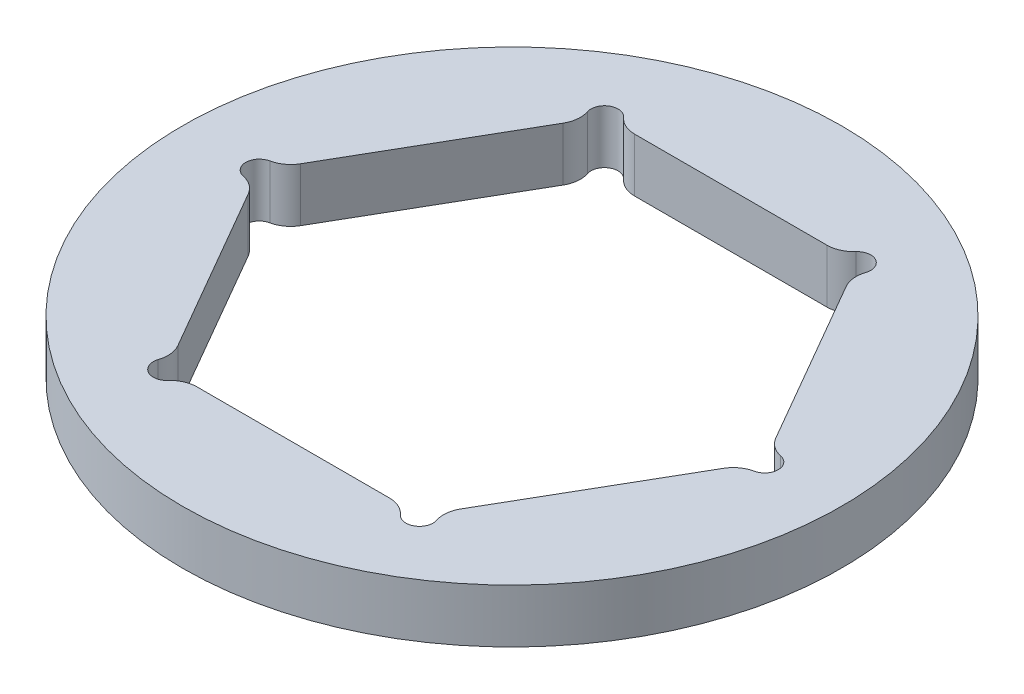
SolidWorks part; units mm, degrees
material "ABS"
ref_plane "Alzado" through (0, 0, 0) normal (0, 0, 1) x (1, 0, 0)
ref_plane "Planta" through (0, 0, 0) normal (0, 1, 0) x (1, 0, 0)
ref_plane "Vista lateral" through (0, 0, 0) normal (1, 0, 0) x (0, 0, -1)
sketch "Croquis1" plane through (0, 0, 0) normal (0, 1, 0) x (1, 0, 0)
  line L1 (4.1867, -5.7024) -> (7.0318, -0.7746)
  line L2 (7.0318, 0.7746) -> (4.1867, 5.7024)
  line L3 (2.8451, 6.477) -> (-2.8451, 6.477)
  line L4 (-4.1867, 5.7024) -> (-7.0318, 0.7746)
  line L5 (-7.0318, -0.7746) -> (-4.1867, -5.7024)
  line L6 (-2.8451, -6.477) -> (2.8451, -6.477)
  circle A0 centre (0, 0) radius 9.7536
  circle A1 centre (0, 0) radius 6.477 construction
  arc A2 (-3.4414, 6.7437) -> (-4.1195, 6.3521) centre (-3.7395, 6.477) ccw
  arc A3 (-3.4414, 6.7437) -> (-2.8451, 6.477) centre (-2.8451, 7.277) ccw
  arc A4 (-4.1867, 5.7024) -> (-4.1195, 6.3521) centre (-4.8795, 6.1024) ccw
  arc A5 (4.1195, 6.3521) -> (3.4414, 6.7437) centre (3.7395, 6.477) ccw
  arc A6 (4.1195, 6.3521) -> (4.1867, 5.7024) centre (4.8795, 6.1024) ccw
  arc A7 (2.8451, 6.477) -> (3.4414, 6.7437) centre (2.8451, 7.277) ccw
  arc A8 (7.5609, -0.3915) -> (7.5609, 0.3915) centre (7.479, 0) ccw
  arc A9 (7.5609, -0.3915) -> (7.0318, -0.7746) centre (7.7246, -1.1746) ccw
  arc A10 (7.0318, 0.7746) -> (7.5609, 0.3915) centre (7.7246, 1.1746) ccw
  arc A11 (3.4414, -6.7437) -> (4.1195, -6.3521) centre (3.7395, -6.477) ccw
  arc A12 (3.4414, -6.7437) -> (2.8451, -6.477) centre (2.8451, -7.277) ccw
  arc A13 (4.1867, -5.7024) -> (4.1195, -6.3521) centre (4.8795, -6.1024) ccw
  arc A14 (-4.1195, -6.3521) -> (-3.4414, -6.7437) centre (-3.7395, -6.477) ccw
  arc A15 (-4.1195, -6.3521) -> (-4.1867, -5.7024) centre (-4.8795, -6.1024) ccw
  arc A16 (-2.8451, -6.477) -> (-3.4414, -6.7437) centre (-2.8451, -7.277) ccw
  arc A17 (-7.5609, 0.3915) -> (-7.5609, -0.3915) centre (-7.479, 0) ccw
  arc A18 (-7.5609, 0.3915) -> (-7.0318, 0.7746) centre (-7.7246, 1.1746) ccw
  arc A19 (-7.0318, -0.7746) -> (-7.5609, -0.3915) centre (-7.7246, -1.1746) ccw
  dimension "D2" = 19.5072
  dimension "D3" = 0.8
  dimension "D4" = 0.8
  dimension "D1" = 12.954
  dimension "D5" = 6
extrude "Saliente-Extruir1" add sketch "Croquis1" along normal mid plane 1.5875
